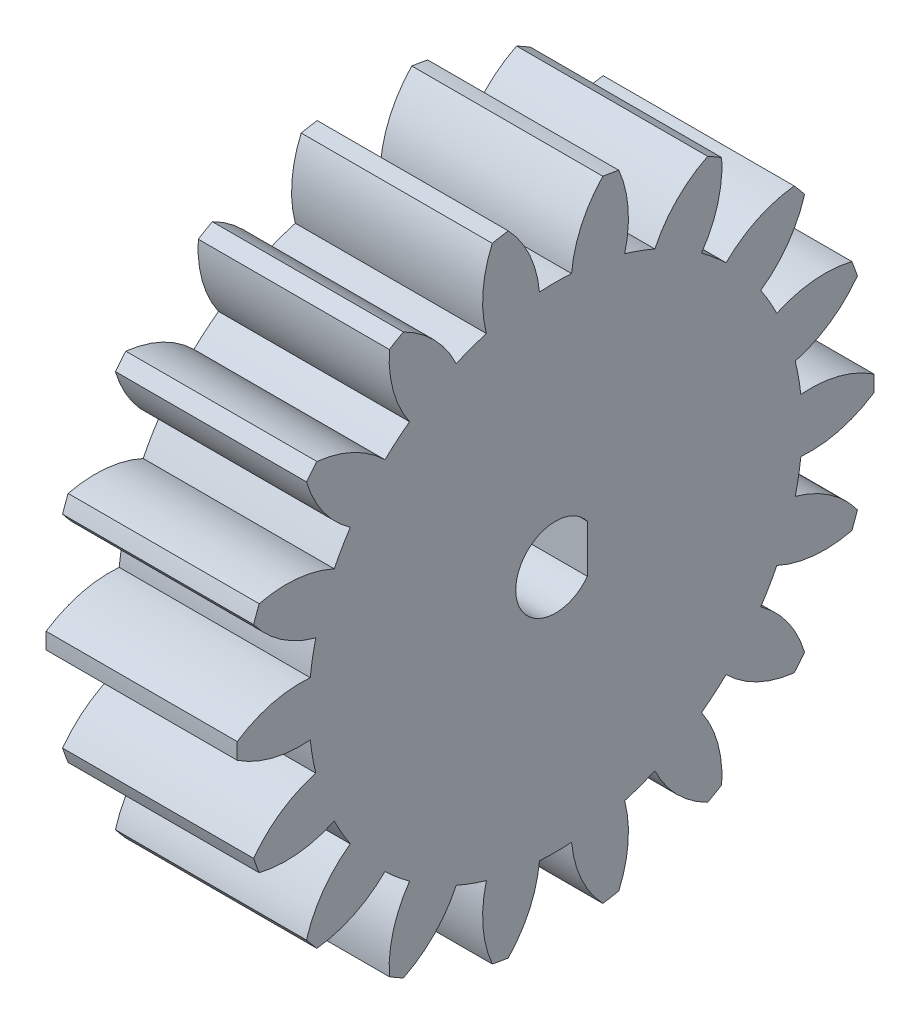
SolidWorks part; units mm, degrees
ref_plane "Plane1" through (0, 0, 0) normal (0, 0, 1) x (1, 0, 0)
ref_plane "Plane2" through (0, 0, 0) normal (0, 1, 0) x (1, 0, 0)
ref_plane "Plane3" through (0, 0, 0) normal (1, 0, 0) x (0, 0, -1)
sketch "HoldingSke" plane through (0, 0, 0) normal (0, 1, 0) x (1, 0, 0)
  line L0 (0, 0) -> (0.4755, -0.1545)
  line L1 (-15, 0) -> (100, 0) construction
  line L2 (0, 0) -> (-2.1039, 2.3779)
  line L3 (0, 0) -> (-11.863, 4.5341)
  line L4 (0, 0) -> (8.2133, 2.6687)
  line L5 (0, 0) -> (-46.8476, -17.4728)
  line L6 (0, 0) -> (-9.9476, -6.7116)
  line L7 (-2.1039, 2.3779) -> (8.6586, 51.2059)
  line L8 (-76.2, 54.61) -> (-76.1, 54.61)
  line L9 (-71.009, 38.7566) -> (-53.1078, 45.2721)
  line L10 (-76.2, 71.12) -> (104.1128, 71.12)
  line L11 (0, 0) -> (-12, 0)
  line L12 (-76.2, 101.6) -> (-76.133, 101.6)
  line L13 (24.9733, 27.94) -> (52.9518, 28.4284)
  line L14 (24.9733, 27.94) -> (24.9743, 27.94)
  line L15 (24.9733, 27.94) -> (100.4006, 29.5858)
  line L16 (-63.627, -2) -> (-12.827, -2)
  circle A0 centre (0, 0) radius 0.1
  circle A1 centre (0, 0) radius 15.499
  circle A2 centre (0, 0) radius 37.5
  circle A3 centre (0, 0) radius 0.1
  dimension "MHD" = 30.998
  dimension "Hub_dia" = 75
  dimension "Bore" = 0.2
  dimension "MBD" = 0.2
  dimension "Num_teeth" = 18
  dimension "Pitch" = 0.5
  dimension "Overall_len" = 50
  dimension "Show_teeth" = 18
  dimension "Thickness" = 12
  dimension "OAL" = 50.0001
  dimension "T_dim" = 0.1
  dimension "Ap" = 20
  dimension "H" = 19.05
  dimension "Pitch_radius" = 180.3128
  dimension "Width" = 12
  dimension "Backlash" = 0.067
  dimension "Addendum_fac" = 1
  dimension "Dedendum_fac" = 1.25
  dimension "Clearance_fac" = 0.25
  dimension "Dedendum_add" = 0.001
  dimension "Module" = 2
sketch "BasProSke" plane through (0, 0, 0) normal (0, 1, 0) x (1, 0, 0)
  line L0 (-10, 0) -> (60, 0) construction
  line L1 (0, 0) -> (0, 20)
  line L2 (0, 0) -> (12, 0)
  line L3 (12, 0) -> (12, 20)
  line L4 (12, 20) -> (0, 20)
  dimension "Thickness" = 12
  dimension "Diameter" = 40
revolve "Base-Revolve" add sketch "BasProSke" angle 360 about L0
sketch "TooCutSke" plane through (0, 0, 0) normal (1, 0, 0) x (0, 0, -1)
  line L1 (0, 0) -> (0, 107) construction
  line L2 (0, 0) -> (-1.686, 17.9209) construction
  line L3 (0, 0) -> (-6.231, 35.3376) construction
  line L4 (-1.686, 17.9209) -> (-3.1155, 17.6688) construction
  arc A0 (1.0078, 15.4662) -> (-1.0078, 15.4662) centre (0, 0) ccw
  arc A1 (2.9913, 19.8007) -> (-2.9913, 19.8007) centre (0, 0) ccw
  circle A2 centre (0, 0) radius 18 construction
  circle A3 centre (0, 0) radius 16.9145 construction
  arc A4 (-1.0078, 15.4662) -> (-2.9913, 19.8007) centre (-8.1775, 14.8063) ccw
  arc A5 (2.9913, 19.8007) -> (1.0078, 15.4662) centre (8.1775, 14.8063) ccw
  dimension "Root_dia" = 30.998
  dimension "Overcut_dia" = 40.0508
  dimension "Pitch_dia" = 36
  dimension "Base_dia" = 33.8289
  dimension "Flank_rad" = 7.2
  dimension "Half_ang" = 10
  dimension "Half_CT" = 1.4516
extrude "ToothCut" cut sketch "TooCutSke" along normal through all
fillet "Breaks" [suppressed] radius 0.04
fillet "RootFillets" [suppressed] radius 0.501
pattern_circular "TeethCuts" count 18 every 20 about axis through (-10, 0, 0) along (1, 0, 0) of "ToothCut", "RootFillets", "Breaks"
sketch "HubNeaOneSke" plane through (0, 0, 0) normal (-1, 0, 0) x (0, 0, 1)
  circle A0 centre (0, 0) radius 15.499
  dimension "Diameter" = 30.998
extrude "HubNearOne" [suppressed] add sketch "HubNeaOneSke" along normal blind 38.0001
sketch "HubNeaBotSke" plane through (0, 0, 0) normal (-1, 0, 0) x (0, 0, 1)
  circle A0 centre (0, 0) radius 15.499
  dimension "Diameter" = 30.998
extrude "HubNearBoth" [suppressed] add sketch "HubNeaBotSke" along normal blind 19
ref_plane "FarPln" through (12, 0, 0) normal (1, 0, 0) x (0, 0, -1)
sketch "HubFarSke" plane through (12, 0, 0) normal (1, 0, 0) x (0, 0, -1)
  circle A0 centre (0, 0) radius 15.499
  dimension "Diameter" = 30.998
extrude "HubFar" [suppressed] add sketch "HubFarSke" along normal blind 19
sketch "BorSke" plane through (0, 0, 0) normal (1, 0, 0) x (0, 0, -1)
  circle A0 centre (0, 0) radius 0.1
  dimension "Diameter" = 0.2
extrude "Bore" cut sketch "BorSke" along normal mid plane 100.0001
sketch "KeySke" plane through (0, 0, 0) normal (1, 0, 0) x (0, 0, -1)
  line L0 (-0.05, 0) -> (-0.05, 0.2)
  line L1 (-0.05, 0.2) -> (0.05, 0.2)
  line L2 (0.05, 0.2) -> (0.05, 0)
  line L3 (0, 0) -> (0, 34) construction
  line L4 (-0.05, 0) -> (0.05, 0)
  dimension "Offset" = 0.2
  dimension "Width" = 0.1
extrude "Keyway" [suppressed] cut sketch "KeySke" along normal mid plane 100.0001
pattern_circular "Keyway2" [suppressed] count 2 every 90 about axis through (-10, 0, 0) along (1, 0, 0)
sketch "Schizzo1" plane through (0, 0, 0) normal (-1, 0, 0) x (0, 0, 1)
  line L0 (-2, 1.5) -> (-2, -1.5)
  arc A0 (-2, -1.5) -> (-2, 1.5) centre (0, 0) ccw
  dimension "D1" = 5
  dimension "D2" = 2
extrude "Taglio-Estrusione1" cut sketch "Schizzo1" against normal blind 13
equation "' \"Module@HoldingSke\" = 6.35"
equation "' \"Num_teeth@HoldingSke\" = 12"
equation "' \"Ap@HoldingSke\" =  20"
equation "' \"Ap@HoldingSke\" = 20"
equation "' \"Width@HoldingSke\" = 0.5 * 25.4"
equation "' \"Hub_dia@HoldingSke\"= 1 * 25.4"
equation "' \"Hub_dia@HoldingSke\" = 1 * 25.4"
equation "' \"Overall_len@HoldingSke\" = 1.0 * 25.4"
equation "' \"Bore@HoldingSke\" = 0.75 * 25.4"
equation "' \"T_dim@HoldingSke\" = 0.1 * 25.4"
equation "' \"Width@KeySke\" = 0.25 * 25.4"
equation "' \"Show_teeth@HoldingSke\" = 13"
equation "' \"Backlash@HoldingSke\" = 0.009 * 25.4"
equation "' \"Addendum_fac@HoldingSke\" = 1.0"
equation "' \"Dedendum_fac@HoldingSke\" = 1.25"
equation "' \"Dedendum_add@HoldingSke\" = 0.00005 * 25.4"
equation "' \"Clearance_fac@HoldingSke\" = 0.25"
equation "\"Pitch@HoldingSke\" = 1 / \"Module@HoldingSke\""
equation "\"Overcut_dia@TooCutSke\" = (\"Num_teeth@HoldingSke\" + 2 * \"Addendum_fac@HoldingSke\") / \"Pitch@HoldingSke\" + 0.002 * 25.4"
equation "\"Pitch_dia@TooCutSke\" = \"Num_teeth@HoldingSke\" / \"Pitch@HoldingSke\""
equation "\"Base_dia@TooCutSke\" = \"Num_teeth@HoldingSke\" / \"Pitch@HoldingSke\" * cos((\"Ap@HoldingSke\"  * 3.14159265 / 180))"
equation "\"Root_dia@TooCutSke\" = (\"Num_teeth@HoldingSke\" + 2) / \"Pitch@HoldingSke\" - 2 * (\"Addendum_fac@HoldingSke\" + \"Dedendum_fac@HoldingSke\") / \"Pitch@HoldingSke\" - \"Dedendum_add@HoldingSke\" * 2"
equation "\"Half_ang@TooCutSke\" = 180 / \"Num_teeth@HoldingSke\""
equation "\"Half_CT@TooCutSke\" = \"Num_teeth@HoldingSke\" / \"Pitch@HoldingSke\" * sin((3.14159265 / 2 / \"Num_teeth@HoldingSke\")) / 2 - 7 * \"Backlash@HoldingSke\" / 4"
equation "\"Flank_rad@TooCutSke\" = \"Num_teeth@HoldingSke\" / \"Pitch@HoldingSke\" / 5"
equation "\"Radius@RootFillets\" = \"Clearance_fac@HoldingSke\" / \"Pitch@HoldingSke\" + \"Dedendum_add@HoldingSke\""
equation "\"Break_rad@Breaks\" = 0.02 / \"Pitch@HoldingSke\""
equation "\"Thickness@HoldingSke\" = \"Width@HoldingSke\""
equation "\"OAL@HoldingSke\" = \"Thickness@HoldingSke\""
equation "\"MHD@HoldingSke\" = (\"Num_teeth@HoldingSke\" + 2) / \"Pitch@HoldingSke\" - 2 * (\"Addendum_fac@HoldingSke\" + \"Dedendum_fac@HoldingSke\")  / \"Pitch@HoldingSke\" - \"Dedendum_add@HoldingSke\" * 2"
equation "\"MBD@HoldingSke\" = (\"Num_teeth@HoldingSke\" + 2) / \"Pitch@HoldingSke\" - 2 * (\"Addendum_fac@HoldingSke\" + \"Dedendum_fac@HoldingSke\")  / \"Pitch@HoldingSke\" - \"Dedendum_add@HoldingSke\" * 2 - 0.002 * 25.4"
equation "\"MHD@HoldingSke\" = ((sgn( \"MHD@HoldingSke\" - \"Hub_dia@HoldingSke\" )-1)*( \"MHD@HoldingSke\" - \"Hub_dia@HoldingSke\" ))/-2+ \"Hub_dia@HoldingSke\""
equation "\"MBD@HoldingSke\" = ((sgn( \"MBD@HoldingSke\" - \"Bore@HoldingSke\" )-1)*( \"MBD@HoldingSke\" - \"Bore@HoldingSke\" ))/-2+ \"Bore@HoldingSke\""
equation "\"OAL@HoldingSke\" = ((sgn( \"OAL@HoldingSke\" - \"Overall_len@HoldingSke\" )+1)*( \"OAL@HoldingSke\" - \"Overall_len@HoldingSke\" ))/2 + \"Overall_len@HoldingSke\" + 0.000002 * 25.4"
equation "\"Num_teeth@TeethCuts\" = int( \"Show_teeth@HoldingSke\" ) + 1"
equation "\"Num_teeth@TeethCuts\" = ((sgn( \"Num_teeth@TeethCuts\" - \"Num_teeth@HoldingSke\" )-1)*( \"Num_teeth@TeethCuts\" - \"Num_teeth@HoldingSke\" ))/-2+ \"Num_teeth@HoldingSke\""
equation "\"Num_teeth@TeethCuts\" = ((sgn( \"Num_teeth@TeethCuts\" - 2.0)+1)*( \"Num_teeth@TeethCuts\" - 2.0))/2 +2.0"
equation "\"Angle@TeethCuts\" = 360.0 / \"Num_teeth@HoldingSke\""
equation "\"Diameter@BasProSke\" = (\"Num_teeth@HoldingSke\" + 2 * \"Addendum_fac@HoldingSke\") / \"Pitch@HoldingSke\""
equation "\"Thickness@BasProSke\"  = \"Thickness@HoldingSke\""
equation "' \"Fillet_rad@BasProSke\" =  \"Thickness@HoldingSke\" * 0.05"
equation "' \"Fillet_rad@BasProSke\" = \"Thickness@HoldingSke\" * 0.05"
equation "\"MHD@HoldingSke\" = ((sgn( \"MHD@HoldingSke\" - \"Root_dia@TooCutSke\" )-1)*( \"MHD@HoldingSke\" - \"Root_dia@TooCutSke\" ))/-2+ \"Root_dia@TooCutSke\""
equation "\"Diameter@HubNeaOneSke\" = \"MHD@HoldingSke\""
equation "\"Length@HubNearOne\" = \"OAL@HoldingSke\" - \"Thickness@BasProSke\""
equation "\"Diameter@HubNeaBotSke\" = \"MHD@HoldingSke\""
equation "\"Length@HubNearBoth\" = ( \"OAL@HoldingSke\" - \"Thickness@BasProSke\" ) / 2.0"
equation "\"Thickness@FarPln\" = \"Thickness@BasProSke\""
equation "\"Diameter@HubFarSke\" = \"MHD@HoldingSke\""
equation "\"Length@HubFar\" = ( \"OAL@HoldingSke\" - \"Thickness@BasProSke\" ) / 2.0"
equation "\"Diameter@BorSke\" = \"MBD@HoldingSke\""
equation "\"D1@Bore\" = \"OAL@HoldingSke\" * 2.0"
equation "\"D1@Keyway\" = \"OAL@HoldingSke\" * 2.0"
equation "\"Offset@KeySke\" = \"T_dim@HoldingSke\" + \"MBD@HoldingSke\" / 2.0"
